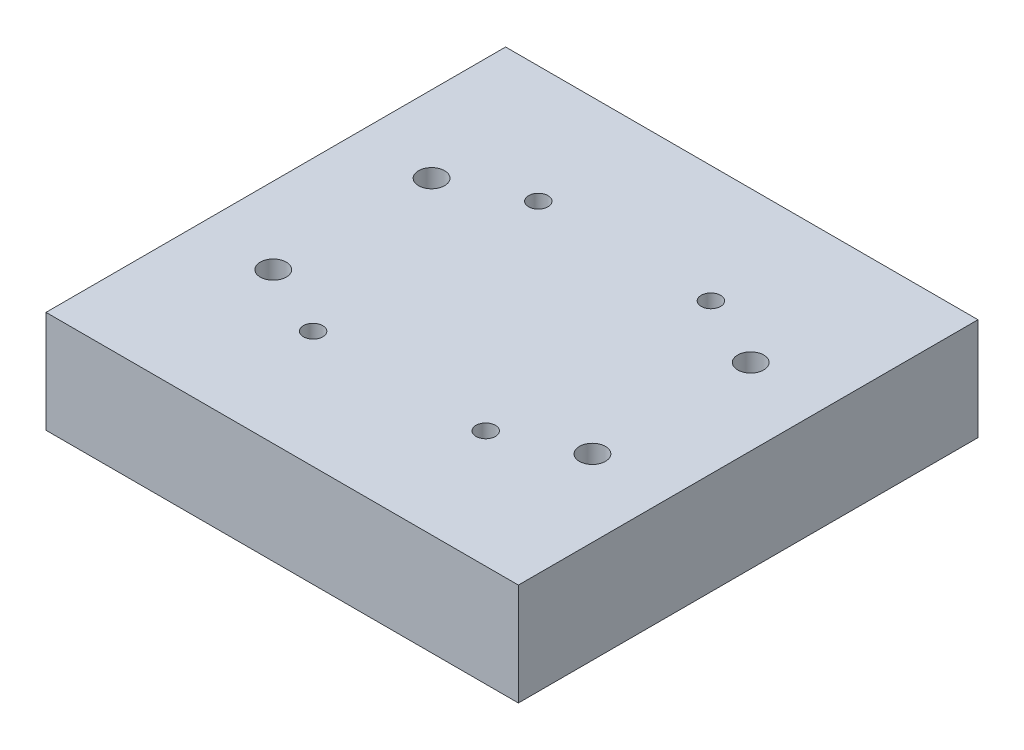
SolidWorks part; units mm, degrees
ref_plane "Front Plane" through (0, 0, 0) normal (0, 0, 1) x (1, 0, 0)
ref_plane "Top Plane" through (0, 0, 0) normal (0, 1, 0) x (1, 0, 0)
ref_plane "Right Plane" through (0, 0, 0) normal (1, 0, 0) x (0, 0, -1)
sketch "Sketch1" plane through (0, 0, 0) normal (0, 1, 0) x (1, 0, 0)
  line L1 (0, 0) -> (234.95, 0)
  line L2 (0, 0) -> (0, 228.6)
  line L3 (0, 228.6) -> (234.95, 228.6)
  line L4 (234.95, 0) -> (234.95, 228.6)
  dimension "D1" = 234.95
  dimension "D2" = 228.6
extrude "Boss-Extrude1" add sketch "Sketch1" along normal blind 50.8
sketch "Sketch2" plane through (0, 50.8, 0) normal (0, 1, 0) x (1, 0, 0)
  line L0 (0, 228.6) -> (0, 0) construction
  line L1 (234.95, 228.6) -> (0, 228.6) construction
  circle A0 centre (74.549, 170.307) radius 4.826
  circle A1 centre (160.401, 170.307) radius 4.826
  circle A2 centre (160.401, 58.293) radius 4.826
  circle A3 centre (74.549, 58.293) radius 4.826
  dimension "D5" = 9.652
  dimension "D1" = 74.549
  dimension "D2" = 58.293
  dimension "D3" = 2
  dimension "D4" = 2
extrude "Cut-Extrude1" cut sketch "Sketch2" against normal blind 38.1
sketch "Sketch3" plane through (0, 50.8, 0) normal (0, 1, 0) x (1, 0, 0)
  line L0 (0, 228.6) -> (0, 0) construction
  line L1 (234.95, 228.6) -> (0, 228.6) construction
  circle A0 centre (196.85, 153.67) radius 6.477
  circle A1 centre (196.85, 74.93) radius 6.477
  circle A2 centre (38.1, 74.93) radius 6.477
  circle A3 centre (38.1, 153.67) radius 6.477
  dimension "D1" = 38.1
  dimension "D2" = 74.93
extrude "Cut-Extrude2" cut sketch "Sketch3" against normal blind 38.1
